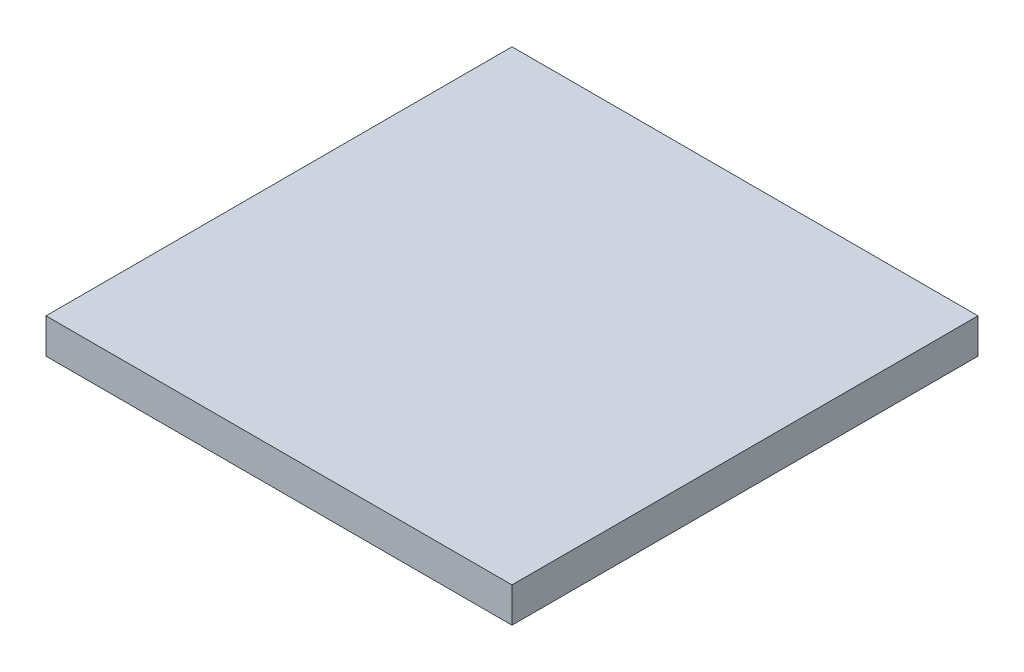
SolidWorks part; units mm, degrees
ref_plane "Front Plane" through (0, 0, 0) normal (0, 0, 1) x (1, 0, 0)
ref_plane "Top Plane" through (0, 0, 0) normal (0, 1, 0) x (1, 0, 0)
ref_plane "Right Plane" through (0, 0, 0) normal (1, 0, 0) x (0, 0, -1)
sketch "Sketch1" plane through (0, 0, 0) normal (0, 1, 0) x (1, 0, 0)
  line L1 (0, 0) -> (101.6, 0)
  line L2 (0, 0) -> (0, -101.6)
  line L3 (0, -101.6) -> (101.6, -101.6)
  line L4 (101.6, 0) -> (101.6, -101.6)
  dimension "D1" = 101.6
  dimension "D2" = 101.6
extrude "Boss-Extrude1" add sketch "Sketch1" along normal blind 7.62
